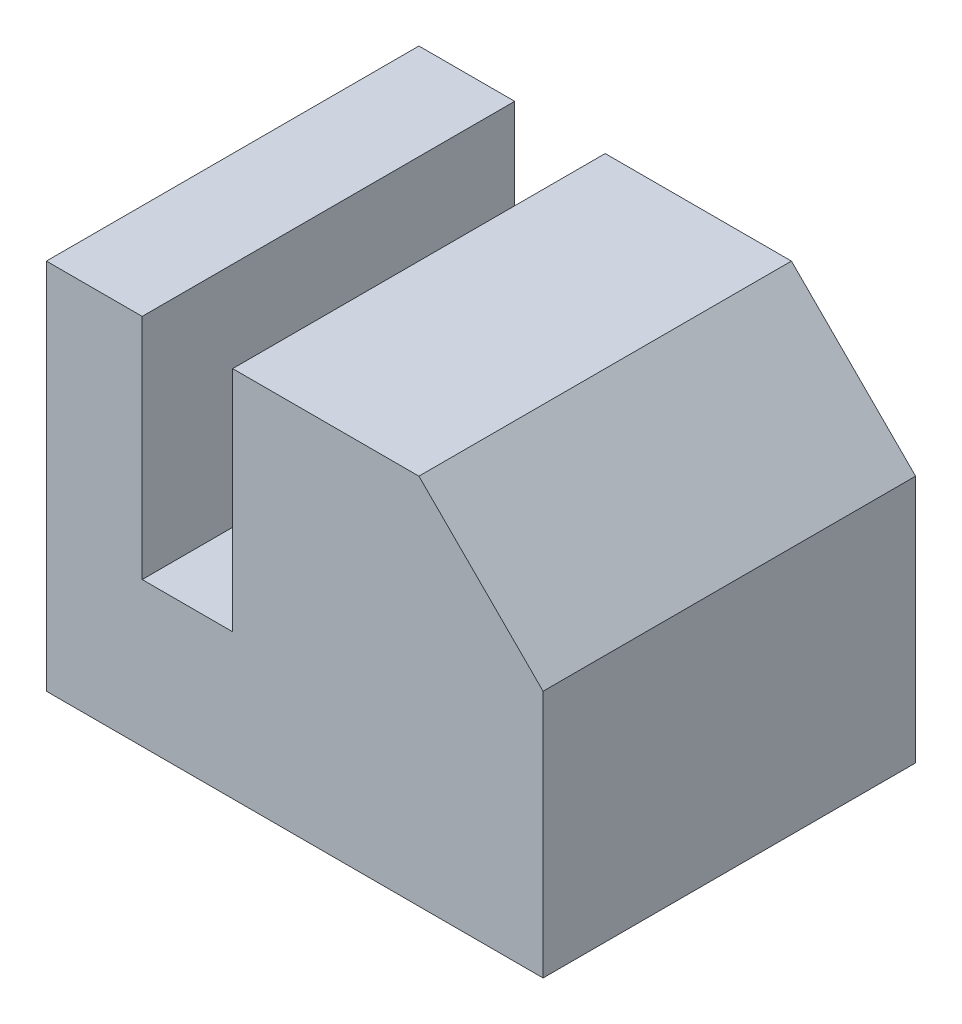
SolidWorks part; units mm, degrees
ref_plane "前基準面" through (0, 0, 0) normal (0, 0, 1) x (1, 0, 0)
ref_plane "上基準面" through (0, 0, 0) normal (0, 1, 0) x (1, 0, 0)
ref_plane "右基準面" through (0, 0, 0) normal (1, 0, 0) x (0, 0, -1)
sketch "草圖1" plane through (0, 0, 0) normal (0, 0, 1) x (1, 0, 0)
  line L1 (-20, 15) -> (20, 15)
  line L2 (-20, 15) -> (-20, -15)
  line L3 (-20, -15) -> (20, -15)
  line L4 (20, 15) -> (20, -15)
  line L5 (-20, 15) -> (20, -15) construction
  line L6 (-20, -15) -> (20, 15) construction
  point P0 (0, 0)
  dimension "D1" = 40
  dimension "D2" = 30
extrude "填料-伸長1" add sketch "草圖1" along normal blind 30
sketch "草圖2" plane through (0, 0, 30) normal (0, 0, 1) x (1, 0, 0)
  line L0 (10, 15) -> (20, 5)
  line L1 (20, 15) -> (-20, 15) construction
  line L2 (20, -15) -> (20, 15) construction
  line L3 (10, 15) -> (20, 15)
  line L4 (20, 15) -> (20, 5)
  dimension "D1" = 10
  dimension "D2" = 10
extrude "除料-伸長1" cut sketch "草圖2" against normal blind 43
sketch "草圖3" plane through (0, 0, 30) normal (0, 0, 1) x (1, 0, 0)
  line L0 (10, 15) -> (-20, 15) construction
  line L1 (-12.2856, 15) -> (-5, 15)
  line L2 (-12.2856, 15) -> (-12.2856, -3.3541)
  line L3 (-12.2856, -3.3541) -> (-5, -3.3541)
  line L4 (-5, 15) -> (-5, -3.3541)
extrude "除料-伸長2" cut sketch "草圖3" against normal up to surface (30 mm away) up to face at (2, 1, 0)
